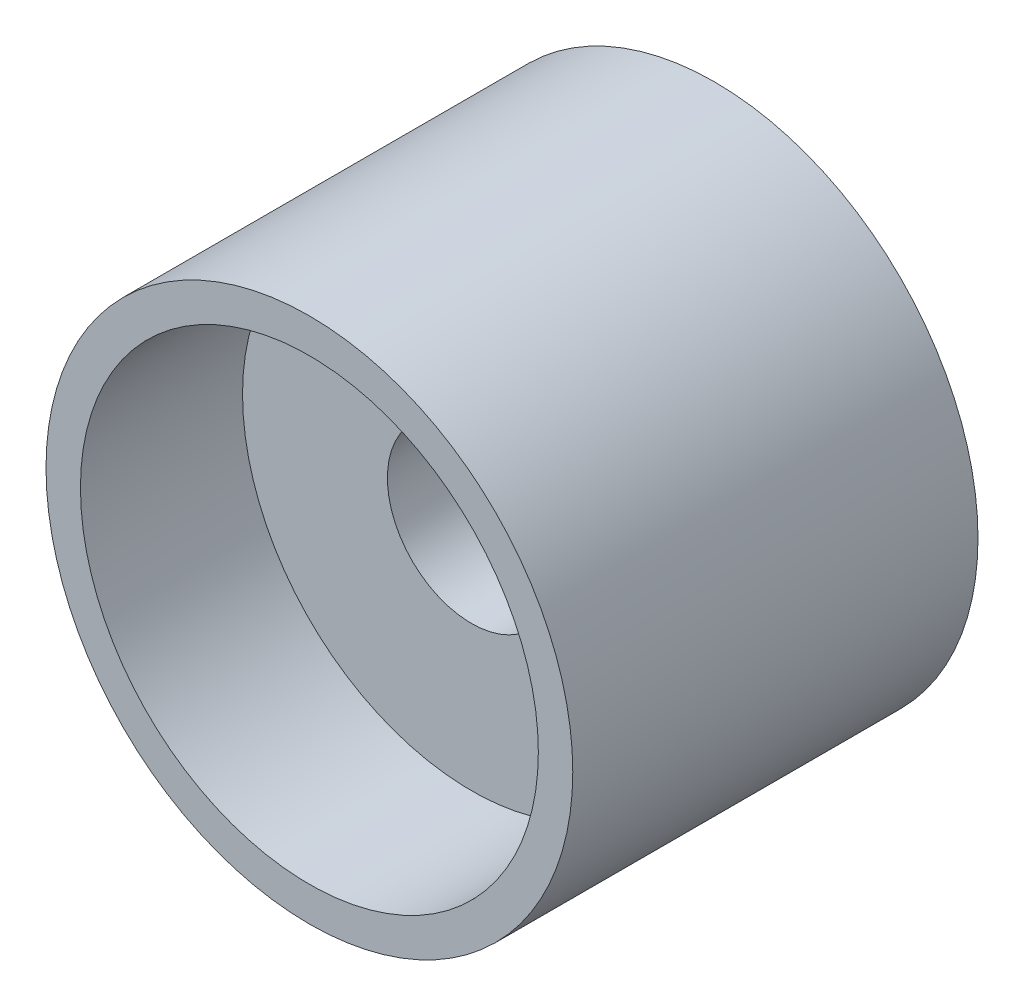
SolidWorks part; units mm, degrees
ref_plane "Front Plane" through (0, 0, 0) normal (0, 0, 1) x (1, 0, 0)
ref_plane "Top Plane" through (0, 0, 0) normal (0, 1, 0) x (1, 0, 0)
ref_plane "Right Plane" through (0, 0, 0) normal (1, 0, 0) x (0, 0, -1)
sketch "Sketch1" plane through (0, 0, 0) normal (0, 0, 1) x (1, 0, 0)
  circle A0 centre (0, 0) radius 13
  circle A1 centre (0, 0) radius 4.15
  dimension "D1" = 26
  dimension "D2" = 8.3
extrude "Boss-Extrude1" add sketch "Sketch1" along normal blind 20
sketch "Sketch2" plane through (0, 0, 20) normal (0, 0, 1) x (1, 0, 0)
  circle A0 centre (0, 0) radius 11.3
  circle A1 centre (0, 0) radius 13 construction
  dimension "D1" = 1.7
extrude "Cut-Extrude1" cut sketch "Sketch2" against normal blind 8
